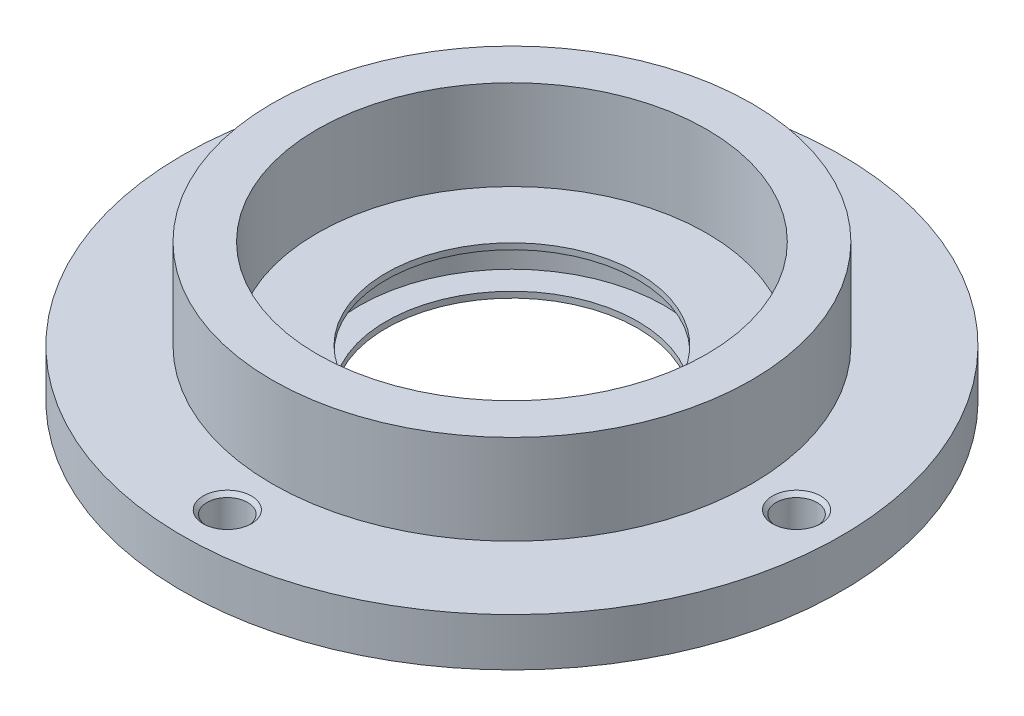
SolidWorks part; units mm, degrees
ref_plane "前视基准面" through (0, 0, 0) normal (0, 0, 1) x (1, 0, 0)
ref_plane "上视基准面" through (0, 0, 0) normal (0, 1, 0) x (1, 0, 0)
ref_plane "右视基准面" through (0, 0, 0) normal (1, 0, 0) x (0, 0, -1)
other "Configuration Table"
sketch "草图1" plane through (0, 0, 0) normal (0, 0, 1) x (1, 0, 0)
  line L0 (0, 34.8163) -> (0, -25.9388) construction
  line L1 (0, 0) -> (55, 0)
  line L2 (55, 0) -> (55, 8)
  line L3 (55, 8) -> (40, 8)
  line L4 (40, 8) -> (40, 23)
  line L5 (40, 23) -> (32.5, 23)
  line L6 (32.5, 23) -> (32.5, 8)
  line L7 (32.5, 8) -> (0, 8)
  line L8 (0, 8) -> (0, 0)
  dimension "D1" = 15
  dimension "D2" = 7.5
  dimension "D3" = 32.5
  dimension "D4" = 8
  dimension "D5" = 55
revolve "旋转1" add sketch "草图1" angle 360 about L8
sketch "草图2" plane through (0, 0, 0) normal (0, 1, 0) x (1, 0, 0)
  circle A0 centre (0, 0) radius 47.5
  circle A1 centre (47.5, 0) radius 4.5
  circle A2 centre (0, -47.5) radius 4.5
  circle A3 centre (-47.5, 0) radius 4.5
  circle A4 centre (0, 47.5) radius 4.5
  point P14 (0, 0)
  dimension "D1" = 4
  dimension "D2" = 95
hole_wizard "M8 螺纹孔1" positions "草图7" profile "草图8" tap size "M8" standard "GB" end condition through all
sketch "草图7" plane through (0, 8, 0) normal (0, 1, 0) x (1, 0, 0)
  point P0 (-47.5, 0)
  point P3 (47.5, 0)
  point P6 (0, -47.5)
  point P9 (0, 47.5)
sketch "草图8" plane through (-47.5, 8, 0) normal (1, 0, 0) x (0, 0, 1)
  line L0 (0, 0) -> (0, 8)
  line L1 (0, 8) -> (3.4, 8)
  line L2 (3.4, 8) -> (3.4, 0.625)
  line L3 (3.4, 0.625) -> (4.025, 0)
  line L5 (4.025, 0) -> (0, 0)
  line L6 (-3.4, 0.625) -> (-4.025, 0) construction
  line L11 (0, -6.35) -> (0, 107.95) construction
  dimension "通孔螺纹孔钻头直径" = 6.8
  dimension "通孔螺纹孔钻头深度" = 8
  dimension "近端锥形沉头孔直径" = 8.05
  dimension "近端锥形沉头孔角度" = 90
cosmetic thread "孔螺蚊线1" parameters "D2"=8
cosmetic thread "孔螺蚊线2" parameters "D2"=8
cosmetic thread "孔螺蚊线3" parameters "D2"=8
cosmetic thread "孔螺蚊线4" parameters "D2"=8
sketch "草图3" plane through (0, 0, 0) normal (0, 1, 0) x (1, 0, 0)
  circle A0 centre (0, 0) radius 21
extrude "切除-拉伸3" cut sketch "草图3" along normal blind 21
sketch "草图4" plane through (0, 0, 0) normal (1, 0, 0) x (0, 0, -1)
  line L0 (0, 0) -> (0, 4)
  line L1 (0, 4) -> (10.5, 4)
  line L2 (25.5, 4) -> (25.5, 1)
  line L3 (25.5, 1) -> (21, 1)
  line L5 (21, 7) -> (25.5, 7)
  line L6 (25.5, 7) -> (25.5, 4)
  line L7 (0, 0) -> (0, 13.0193) construction
  line L8 (21, 7) -> (10.5, 7)
  line L9 (0, 7) -> (0, 1)
  line L10 (10.5, 7) -> (10.5, 1)
  line L11 (10.5, 1) -> (21, 1)
revolve "切除-旋转2" cut sketch "草图4" angle 360 about L7
